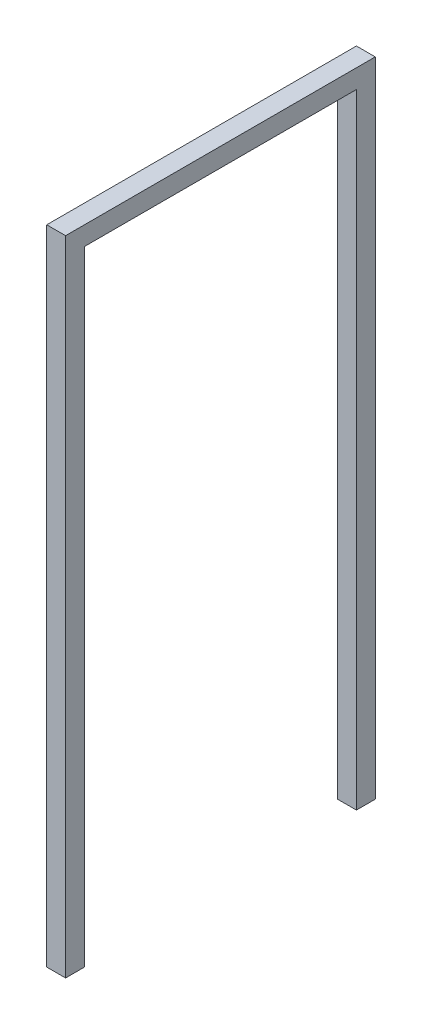
SolidWorks part; units mm, degrees
ref_plane "Alzado" through (0, 0, 0) normal (0, 0, 1) x (1, 0, 0)
ref_plane "Planta" through (0, 0, 0) normal (0, 1, 0) x (1, 0, 0)
ref_plane "Vista lateral" through (0, 0, 0) normal (1, 0, 0) x (0, 0, -1)
sketch "Croquis1" plane through (0, 0, 0) normal (0, 1, 0) x (1, 0, 0)
  line L0 (76.2, 0) -> (1481.2, 0) construction
  line L1 (0, 0) -> (76.2, 0)
  line L2 (0, 0) -> (0, -76.2)
  line L3 (0, -76.2) -> (76.2, -76.2)
  line L4 (76.2, 0) -> (76.2, -76.2)
  line L5 (1557.4, 0) -> (2962.4, 0) construction
  line L6 (1481.2, 0) -> (1557.4, 0)
  line L7 (1481.2, 0) -> (1481.2, -76.2)
  line L8 (1481.2, -76.2) -> (1557.4, -76.2)
  line L9 (1557.4, 0) -> (1557.4, -76.2)
  line L10 (3038.6, 0) -> (4443.6, 0) construction
  line L11 (2962.4, 0) -> (3038.6, 0)
  line L12 (2962.4, 0) -> (2962.4, -76.2)
  line L13 (2962.4, -76.2) -> (3038.6, -76.2)
  line L14 (3038.6, 0) -> (3038.6, -76.2)
  line L15 (4519.8, 0) -> (5924.8, 0) construction
  line L16 (4443.6, 0) -> (4519.8, 0)
  line L17 (4443.6, 0) -> (4443.6, -76.2)
  line L18 (4443.6, -76.2) -> (4519.8, -76.2)
  line L19 (4519.8, 0) -> (4519.8, -76.2)
  line L20 (0, -76.2) -> (0, -626.2) construction
  line L21 (5924.8, 0) -> (6001, 0)
  line L22 (5924.8, 0) -> (5924.8, -76.2)
  line L23 (5924.8, -76.2) -> (6001, -76.2)
  line L24 (6001, 0) -> (6001, -76.2)
  line L25 (0, -626.2) -> (6001, -626.2) construction
  line L26 (4519.8, -1252.4) -> (5924.8, -1252.4) construction
  line L27 (3038.6, -1252.4) -> (4443.6, -1252.4) construction
  line L28 (1557.4, -1252.4) -> (2962.4, -1252.4) construction
  line L29 (76.2, -1252.4) -> (1481.2, -1252.4) construction
  line L30 (6001, -626.2) -> (6001, -76.2) construction
  line L31 (6001, -1252.4) -> (6001, -1176.2)
  line L32 (5924.8, -1176.2) -> (6001, -1176.2)
  line L33 (5924.8, -1252.4) -> (5924.8, -1176.2)
  line L34 (5924.8, -1252.4) -> (6001, -1252.4)
  line L35 (4519.8, -1252.4) -> (4519.8, -1176.2)
  line L36 (4443.6, -1176.2) -> (4519.8, -1176.2)
  line L37 (4443.6, -1252.4) -> (4443.6, -1176.2)
  line L38 (4443.6, -1252.4) -> (4519.8, -1252.4)
  line L39 (3038.6, -1252.4) -> (3038.6, -1176.2)
  line L40 (2962.4, -1176.2) -> (3038.6, -1176.2)
  line L41 (2962.4, -1252.4) -> (2962.4, -1176.2)
  line L42 (2962.4, -1252.4) -> (3038.6, -1252.4)
  line L43 (1557.4, -1252.4) -> (1557.4, -1176.2)
  line L44 (1481.2, -1176.2) -> (1557.4, -1176.2)
  line L45 (1481.2, -1252.4) -> (1481.2, -1176.2)
  line L46 (1481.2, -1252.4) -> (1557.4, -1252.4)
  line L47 (76.2, -1252.4) -> (76.2, -1176.2)
  line L48 (0, -1176.2) -> (76.2, -1176.2)
  line L49 (0, -1252.4) -> (0, -1176.2)
  line L50 (0, -1252.4) -> (76.2, -1252.4)
  dimension "D1" = 76.2
  dimension "D2" = 76.2
  dimension "D3" = 1405
  dimension "D4" = 76.2
  dimension "D5" = 76.2
  dimension "D6" = 1405
  dimension "D7" = 76.2
  dimension "D8" = 76.2
  dimension "D9" = 1405
  dimension "D10" = 76.2
  dimension "D11" = 76.2
  dimension "D12" = 1405
  dimension "D13" = 76.2
  dimension "D14" = 76.2
  dimension "D15" = 550
extrude "Saliente-Extruir1" add sketch "Croquis1" along normal blind 2600
sketch "Croquis2" plane through (0, 0, 76.2) normal (0, 0, 1) x (1, 0, 0)
  line L0 (76.2, 2600) -> (76.2, 0) construction
  line L1 (0, 2600) -> (76.2, 2600)
  line L2 (0, 2600) -> (0, 2523.8)
  line L3 (0, 2523.8) -> (76.2, 2523.8)
  line L4 (76.2, 2600) -> (76.2, 2523.8)
  line L5 (1557.4, 2600) -> (1557.4, 0) construction
  line L6 (1481.2, 2600) -> (1557.4, 2600)
  line L7 (1481.2, 2600) -> (1481.2, 2523.8)
  line L8 (1481.2, 2523.8) -> (1557.4, 2523.8)
  line L9 (1557.4, 2600) -> (1557.4, 2523.8)
  line L10 (3038.6, 2600) -> (3038.6, 0) construction
  line L11 (2962.4, 2600) -> (3038.6, 2600)
  line L12 (2962.4, 2600) -> (2962.4, 2523.8)
  line L13 (2962.4, 2523.8) -> (3038.6, 2523.8)
  line L14 (3038.6, 2600) -> (3038.6, 2523.8)
  line L15 (4519.8, 2600) -> (4519.8, 0) construction
  line L16 (4443.6, 2600) -> (4519.8, 2600)
  line L17 (4443.6, 2600) -> (4443.6, 2523.8)
  line L18 (4443.6, 2523.8) -> (4519.8, 2523.8)
  line L19 (4519.8, 2600) -> (4519.8, 2523.8)
  line L20 (6001, 2600) -> (6001, 0) construction
  line L21 (5924.8, 2600) -> (6001, 2600)
  line L22 (5924.8, 2600) -> (5924.8, 2523.8)
  line L23 (5924.8, 2523.8) -> (6001, 2523.8)
  line L24 (6001, 2600) -> (6001, 2523.8)
  dimension "D1" = 76.2
  dimension "D2" = 76.2
  dimension "D3" = 76.2
extrude "Saliente-Extruir2" add sketch "Croquis2" along normal up to surface (1100 mm away) up to face at (5962.9, 1300, 1176.2)
sketch "Croquis3" plane through (6001, 0, 0) normal (1, 0, 0) x (0, 0, -1)
  line L1 (-1252.4, 0) -> (0, 0)
  line L2 (-1252.4, 0) -> (-1252.4, 2600)
  line L3 (-1252.4, 2600) -> (0, 2600)
  line L4 (0, 0) -> (0, 2600)
extrude "Cortar-Extruir1" cut sketch "Croquis3" against normal up to surface (5924.8 mm away) up to face at (76.2, 1280.95, 626.2)
